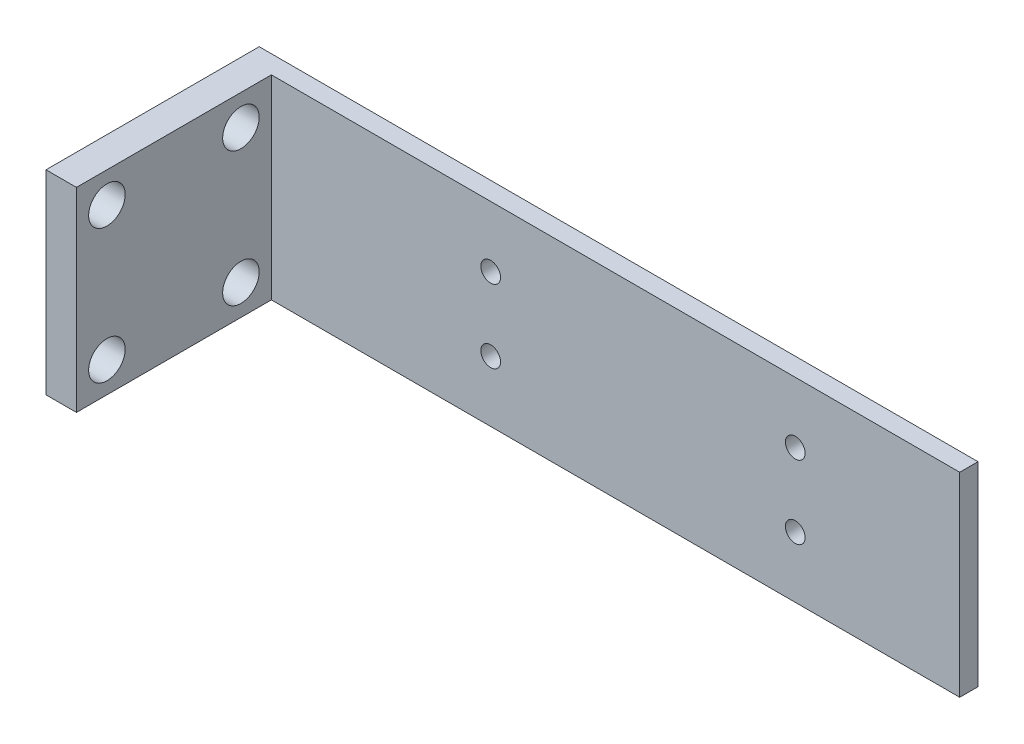
SolidWorks part; units mm, degrees
ref_plane "前视基准面" through (0, 0, 0) normal (0, 0, 1) x (1, 0, 0)
ref_plane "上视基准面" through (0, 0, 0) normal (0, 1, 0) x (1, 0, 0)
ref_plane "右视基准面" through (0, 0, 0) normal (1, 0, 0) x (0, 0, -1)
sketch "草图1" plane through (0, 0, 0) normal (0, 0, 1) x (1, 0, 0)
  line L1 (-71.2816, 22.717) -> (46.7184, 22.717)
  line L2 (-71.2816, 22.717) -> (-71.2816, -9.283)
  line L3 (-71.2816, -9.283) -> (46.7184, -9.283)
  line L4 (46.7184, 22.717) -> (46.7184, -9.283)
  dimension "D1" = 118
  dimension "D2" = 32
extrude "凸台-拉伸1" add sketch "草图1" along normal blind 3
sketch "草图2" plane through (0, 0, 3) normal (0, 0, 1) x (1, 0, 0)
  line L0 (-71.2816, 22.717) -> (-71.2816, -9.283) construction
  line L1 (46.7184, 22.717) -> (-71.2816, 22.717) construction
  line L2 (-71.2816, -9.283) -> (46.7184, -9.283) construction
  circle A0 centre (-30.2816, 12.717) radius 1.62
  circle A1 centre (-30.2816, 0.717) radius 1.62
  circle A2 centre (19.7184, 12.717) radius 1.62
  circle A3 centre (19.7184, 0.717) radius 1.62
  dimension "D1" = 3.24
  dimension "D2" = 41
  dimension "D3" = 10
  dimension "D4" = 3.24
  dimension "D5" = 10
  dimension "D6" = 41
  dimension "D7" = 3.24
  dimension "D8" = 50
  dimension "D9" = 3.24
extrude "切除-拉伸1" cut sketch "草图2" against normal blind 3
sketch "草图3" plane through (0, 0, 3) normal (0, 0, 1) x (1, 0, 0)
  line L0 (-71.2816, -9.283) -> (46.7184, -9.283) construction
  line L1 (-71.2816, 22.717) -> (-66.2816, 22.717)
  line L2 (-71.2816, 22.717) -> (-71.2816, -9.283)
  line L3 (-71.2816, -9.283) -> (-66.2816, -9.283)
  line L4 (-66.2816, 22.717) -> (-66.2816, -9.283)
  dimension "D1" = 5
extrude "凸台-拉伸2" add sketch "草图3" along normal blind 32
sketch "草图4" plane through (-71.2816, 0, 0) normal (-1, 0, 0) x (0, 0, 1)
  line L0 (35, 22.717) -> (35, -9.283) construction
  line L1 (35, 22.717) -> (0, 22.717) construction
  line L2 (35, -9.283) -> (0, -9.283) construction
  line L3 (0, 22.717) -> (0, -9.283) construction
  circle A0 centre (30, 17.717) radius 3
  circle A1 centre (30, -4.283) radius 3
  circle A2 centre (8, 17.717) radius 3
  circle A3 centre (8, -4.283) radius 3
  dimension "D1" = 5
  dimension "D3" = 5
  dimension "D4" = 5
  dimension "D5" = 8
  dimension "D2" = 5
extrude "切除-拉伸2" cut sketch "草图4" against normal blind 32
